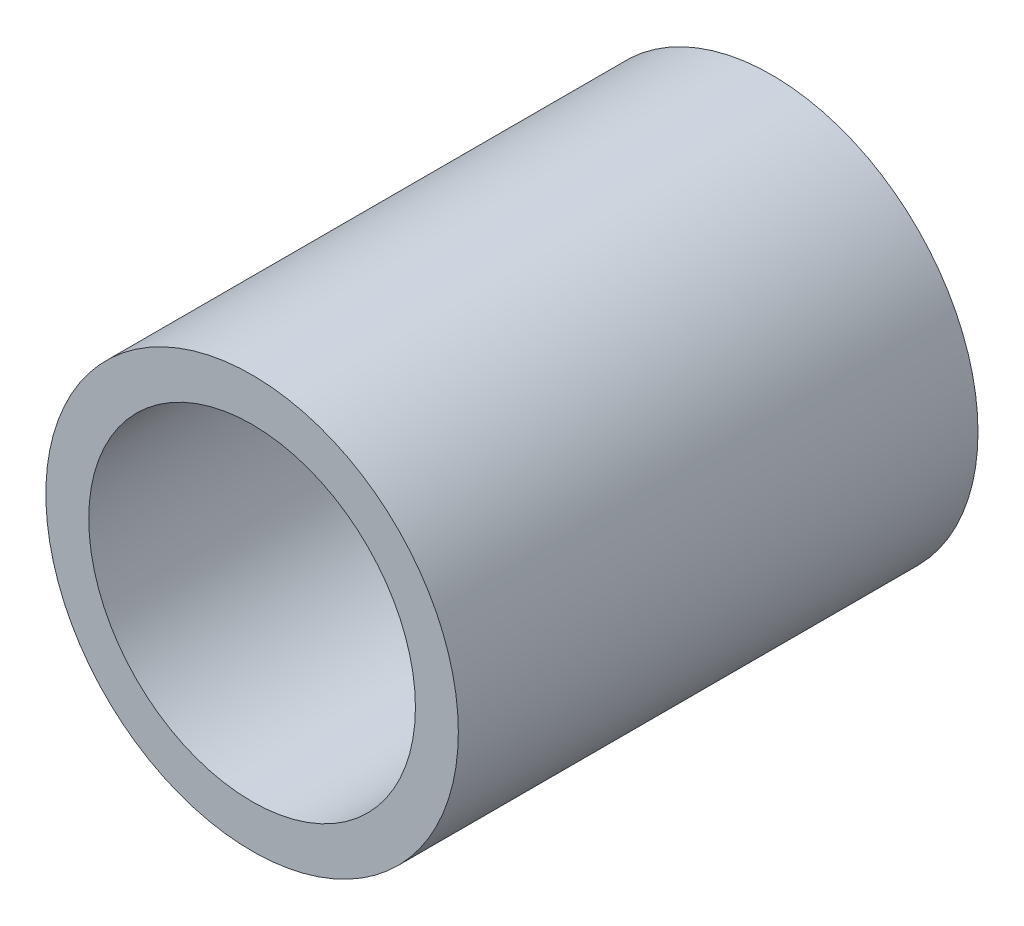
SolidWorks part; units mm, degrees
material "AISI 1020"
ref_plane "Front Plane" through (0, 0, 0) normal (0, 0, 1) x (1, 0, 0)
ref_plane "Top Plane" through (0, 0, 0) normal (0, 1, 0) x (1, 0, 0)
ref_plane "Right Plane" through (0, 0, 0) normal (1, 0, 0) x (0, 0, -1)
sketch "Sketch1" plane through (0, 0, 0) normal (0, 0, 1) x (1, 0, 0)
  circle A0 centre (0, 0) radius 7.9375
  circle A1 centre (0, 0) radius 6.2865
  dimension "D1" = 15.875
  dimension "D2" = 1.651
extrude "Boss-Extrude1" add sketch "Sketch1" along normal blind 20
